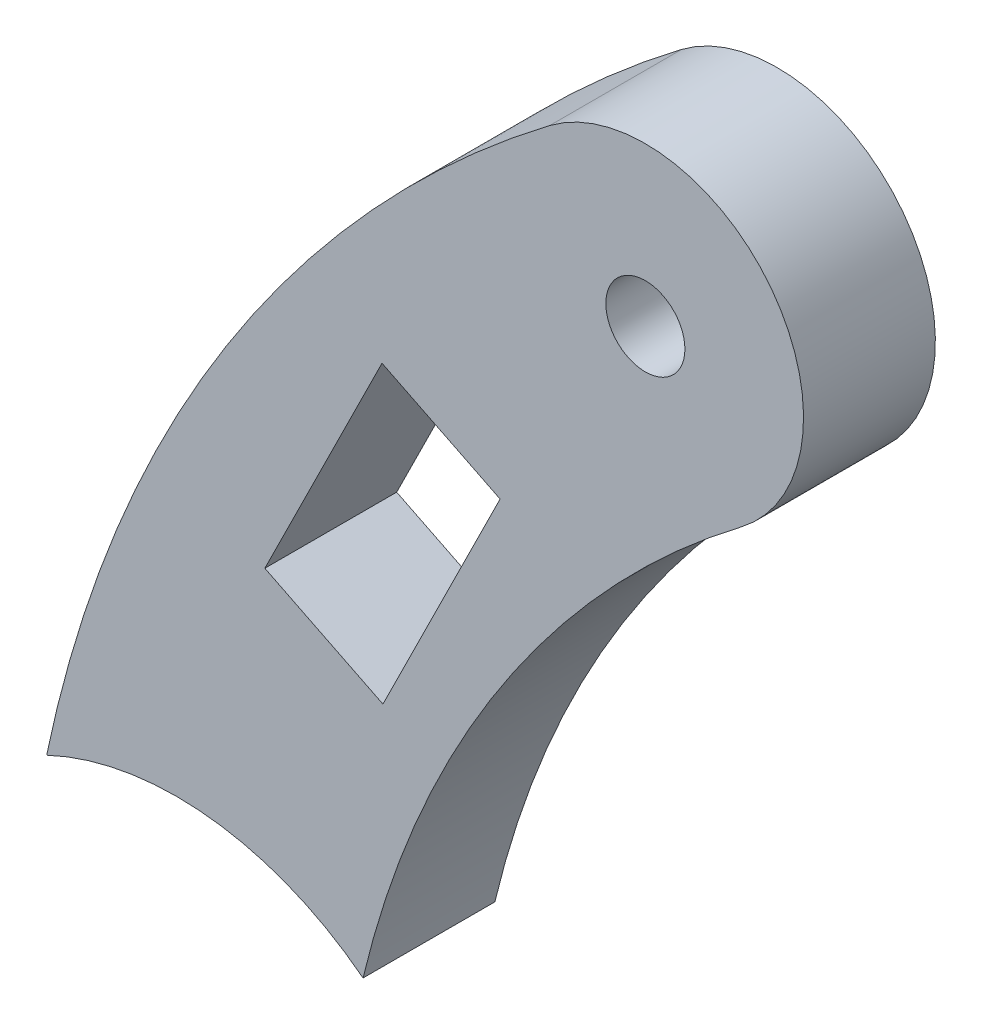
SolidWorks part; units mm, degrees
ref_plane "Plan de face" through (0, 0, 0) normal (0, 0, 1) x (1, 0, 0)
ref_plane "Plan de dessus" through (0, 0, 0) normal (0, 1, 0) x (1, 0, 0)
ref_plane "Plan de droite" through (0, 0, 0) normal (1, 0, 0) x (0, 0, -1)
sketch "Esquisse1" plane through (0, 0, 0) normal (0, 0, 1) x (1, 0, 0)
  line L0 (-27.2222, 35.8323) -> (0, 0) construction
  line L1 (0, 0) -> (-45, 0) construction
  line L2 (-46.8104, 4.6506) -> (-32.0684, 34.3641) construction
  line L3 (0, 0) -> (-40.3113, 20) construction
  line L4 (-41.655, 20.6667) -> (-37.176, 18.4444)
  line L5 (-37.176, 18.4444) -> (-32.7315, 27.4025)
  line L6 (-32.7315, 27.4025) -> (-37.2106, 29.6247)
  line L7 (-37.2106, 29.6247) -> (-41.655, 20.6667)
  arc A0 (-45, 0) -> (-27.2222, 35.8323) centre (0, 0) cw construction
  arc A1 (-30.8519, 40.6099) -> (-49.9306, 10.3894) centre (0, 0) ccw
  arc A2 (-23.5926, 31.0546) -> (-37.9306, 9.0704) centre (0, 0) ccw
  arc A3 (-23.5926, 31.0546) -> (-30.8519, 40.6099) centre (-27.2222, 35.8323) ccw
  arc A4 (-49.9306, 10.3894) -> (-37.9306, 9.0704) centre (-45, 0) cw
  circle A5 centre (-27.2222, 35.8323) radius 1.5
  circle A6 centre (-45, 0) radius 1.5 construction
  circle A7 centre (-45, 0) radius 11.5 construction
  dimension "D1" = 40
  dimension "D2" = 3
  dimension "D3" = 6
  dimension "D4" = 45
  dimension "D6" = 23
  dimension "D7" = 51
  dimension "D8" = 39
  dimension "D5" = 1
  dimension "D9" = 0
  dimension "D10" = 10
  dimension "D11" = 5
extrude "Boss.-Extru.1" add sketch "Esquisse1" along normal blind 5
